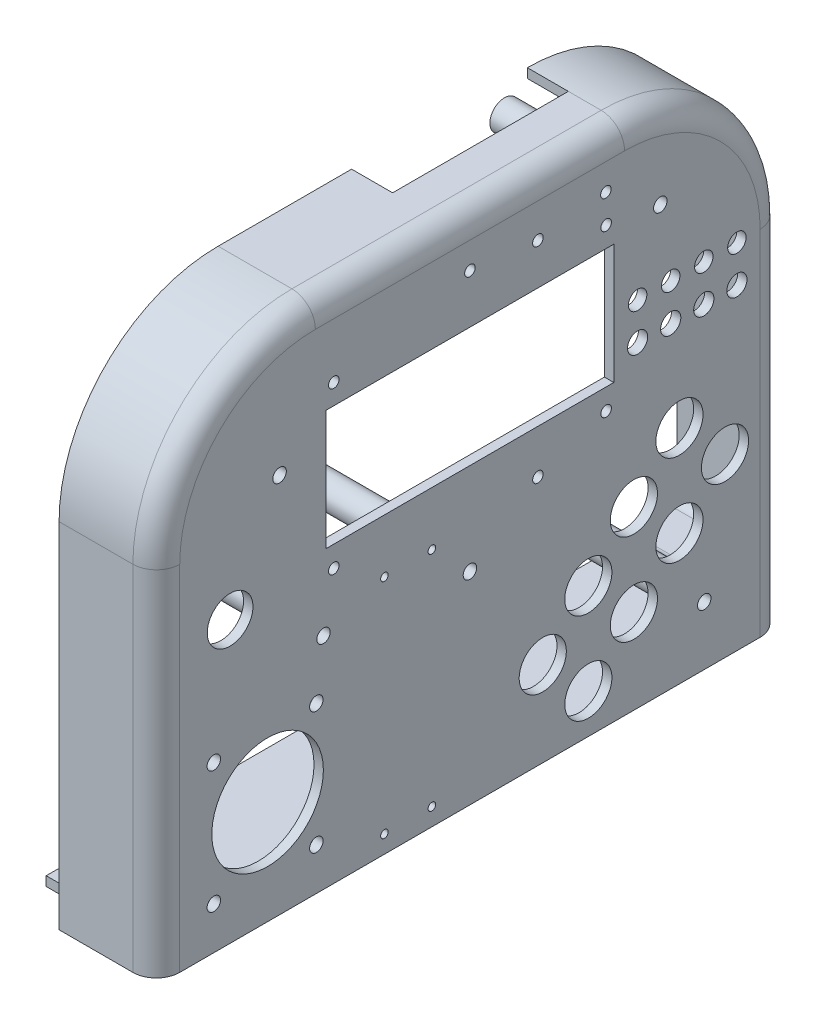
SolidWorks part; units mm, degrees
ref_plane "Front Plane" through (0, 0, 0) normal (0, 0, 1) x (1, 0, 0)
ref_plane "Top Plane" through (0, 0, 0) normal (0, 1, 0) x (1, 0, 0)
ref_plane "Right Plane" through (0, 0, 0) normal (1, 0, 0) x (0, 0, -1)
sketch "Sketch1" plane through (0, 0, 0) normal (1, 0, 0) x (0, 0, -1)
  line L0 (-107.09, -0.1) -> (107.09, -0.1) construction
  line L1 (-49.1, -20.45) -> (49.1, -20.45)
  line L2 (-49.1, -20.45) -> (-49.1, 20.45)
  line L3 (-49.1, 20.45) -> (49.1, 20.45)
  line L4 (49.1, -20.45) -> (49.1, 20.45)
  line L5 (-49.1, -20.45) -> (49.1, 20.45) construction
  line L6 (-49.1, 20.45) -> (49.1, -20.45) construction
  line L11 (-49.1, 29.95) -> (49.1, 29.95) construction
  line L12 (-49.1, 29.95) -> (-49.1, -30.15) construction
  line L13 (-49.1, -30.15) -> (49.1, -30.15) construction
  line L14 (49.1, 29.95) -> (49.1, -30.15) construction
  line L15 (-49.1, 20.45) -> (-82.6403, 20.45) construction
  line L16 (0, 0) -> (0, -0.1) construction
  line L17 (-46.5, -27.6) -> (46.5, -27.6) construction
  line L18 (-46.5, -27.6) -> (-46.5, 27.4) construction
  line L19 (-46.5, 27.4) -> (46.5, 27.4) construction
  line L20 (46.5, -27.6) -> (46.5, 27.4) construction
  line L21 (-46.5, -27.6) -> (46.5, 27.4) construction
  line L22 (-46.5, 27.4) -> (46.5, -27.6) construction
  line L23 (55.9773, -60.6563) -> (87.09, -60.6563) construction
  line L24 (71.5337, -45.1) -> (87.09, -60.6563) construction
  line L25 (55.9773, -60.6563) -> (71.5337, -45.1) construction
  line L26 (0, -0.1) -> (-71.6, -0.1) construction
  line L31 (0, -120.8) -> (0, 54.2) construction
  line L32 (-52.79, 54.2) -> (52.79, 54.2)
  line L33 (-69.95, -85.45) -> (-69.1, -85.45) construction
  line L34 (-52.45, -106.35) -> (-87.45, -106.35) construction
  line L35 (-52.45, -106.35) -> (-52.45, -64.55) construction
  line L36 (-52.45, -64.55) -> (-87.45, -64.55) construction
  line L37 (-87.45, -106.35) -> (-87.45, -64.55) construction
  line L38 (-52.45, -106.35) -> (-87.45, -64.55) construction
  line L39 (-52.45, -64.55) -> (-87.45, -106.35) construction
  line L40 (-107.09, -0.1) -> (-107.09, -120.8)
  line L41 (-107.09, -120.8) -> (107.09, -120.8)
  line L42 (107.09, -0.1) -> (107.09, -120.8)
  line L43 (0, -45.5) -> (0, -51.55) construction
  line L51 (46.42, 54.2) -> (46.42, 37.2) construction
  line L52 (0, 37.2) -> (46.42, 37.2) construction
  line L53 (23.21, 37.2) -> (23.21, -27.6) construction
  line L54 (-52.45, -106.35) -> (0, -106.35) construction
  line L56 (-29.2, -38.8) -> (-13, -38.8) construction
  line L58 (-29.2, -114.8) -> (-13, -114.8) construction
  line L59 (-29.2, -114.8) -> (-29.2, -38.8) construction
  line L60 (-29.2, -38.8) -> (-13, -38.8) construction
  line L61 (-13, -114.8) -> (-13, -38.8) construction
  line L62 (-29.2, -114.8) -> (-13, -38.8) construction
  line L63 (-29.2, -38.8) -> (-13, -114.8) construction
  line L65 (91.15, -3.25) -> (91.15, -9.25) construction
  circle A0 centre (46.5, 27.4) radius 1.8
  circle A1 centre (-46.5, -27.6) radius 1.8
  circle A2 centre (-46.5, 27.4) radius 1.8
  circle A3 centre (46.5, -27.6) radius 1.8
  circle A4 centre (57.25, -0.1) radius 3.15
  circle A5 centre (68.55, -0.1) radius 3.15
  circle A6 centre (79.85, -0.1) radius 3.15
  circle A7 centre (91.15, -0.1) radius 3.15
  circle A9 centre (46.5, 27.4) radius 2.55 construction
  circle A10 centre (46.5, -27.6) radius 2.55 construction
  circle A11 centre (71.5337, -45.1) radius 8.05
  circle A12 centre (87.09, -60.6563) radius 8.05
  circle A13 centre (71.5337, -76.2127) radius 8.05
  circle A14 centre (55.9773, -91.769) radius 8.05
  circle A15 centre (40.421, -107.3254) radius 8.05
  circle A16 centre (55.9773, -60.6563) radius 8.05
  circle A17 centre (40.421, -76.2127) radius 8.05
  circle A18 centre (24.8646, -91.769) radius 8.05
  circle A25 centre (-87.45, -106.35) radius 2.3
  circle A26 centre (-52.45, -106.35) radius 2.3
  circle A27 centre (-52.45, -64.55) radius 2.3
  circle A28 centre (-87.45, -64.55) radius 2.3
  circle A29 centre (-69.1, -85.45) radius 19.05
  arc A30 (52.79, 54.2) -> (107.09, -0.1) centre (52.79, -0.1) cw
  arc A31 (-52.79, 54.2) -> (-107.09, -0.1) centre (-52.79, -0.1) ccw
  circle A41 centre (-81.9, -25.1) radius 7.8
  circle A44 centre (46.42, 37.2) radius 1.8
  circle A45 centre (0, 37.2) radius 1.8
  circle A46 centre (23.21, 34.55) radius 1.8
  circle A47 centre (23.21, -35.45) radius 1.8
  circle A48 centre (-29.2, -38.8) radius 1.3
  circle A49 centre (-13, -38.8) radius 1.3
  circle A50 centre (-13, -114.8) radius 1.3
  circle A51 centre (-29.2, -114.8) radius 1.3
  circle A52 centre (91.15, -12.7) radius 3.45
  circle A53 centre (79.85, -12.7) radius 3.45
  circle A54 centre (68.55, -12.7) radius 3.45
  circle A55 centre (57.25, -12.7) radius 3.45
  point P1 (0, 0)
  point P11 (46.5, 27.4)
  point P12 (-46.5, -27.6)
  point P16 (-48.3, -27.6)
  point P17 (-46.5, -29.4)
  point P18 (48.3, 27.4)
  point P19 (46.5, 29.2)
  point P22 (-46.5, 29.2)
  point P23 (-48.3, 27.4)
  point P26 (46.5, -29.4)
  point P27 (48.3, -27.6)
  point P30 (54.1, -0.1)
  point P31 (60.4, -0.1)
  point P32 (57.25, 3.05)
  point P36 (65.4, -0.1)
  point P37 (71.7, -0.1)
  point P40 (76.7, -0.1)
  point P41 (83, -0.1)
  point P44 (88, -0.1)
  point P45 (88, -0.1)
  point P47 (-74.1, -25.1)
  point P48 (-64.1, -0.1)
  point P49 (-71.6, 7.4)
  point P52 (0, -0.1)
  point P67 (71.5337, -45.1)
  point P84 (-82.6403, 12.7)
  point P86 (0, -0.1)
  point P92 (0, -33.3)
  point P96 (-69.95, -85.45)
  point P97 (-52.45, -64.55)
  point P98 (-87.45, -64.55)
  point P99 (-87.45, -106.35)
  point P100 (-52.45, -106.35)
  point P107 (0, -45.5)
  point P108 (-81.9, 7.7)
  point P109 (0, 0)
  point P110 (0, 0)
  point P111 (57.25, -0.1)
  point P112 (57.25, -0.1)
  point P116 (-71.6, 7.4)
  point P119 (-74.1, -25.1)
  point P120 (-81.9, -17.3)
  point P123 (23.21, 37.2)
  point P124 (0, 37.2)
  point P125 (0, -33.3)
  point P126 (0, 0)
  point P127 (46.42, 37.2)
  point P134 (-26.225, -106.35)
  point P136 (-81.9, -32.9)
  point P141 (-21.1, -38.8)
  point P147 (-21.1, -76.8)
  point P155 (60.7, -12.7)
  point P156 (65.1, -12.7)
  point P157 (72, -12.7)
  point P158 (76.4, -12.7)
  point P159 (83.3, -12.7)
  point P160 (87.7, -12.7)
  point P161 (61.6695, -54.9641)
  point P162 (65, -56.4773)
  point P163 (65.8414, -50.7922)
  point P164 (71.5337, -53.15)
  point P165 (0, 0)
  point P166 (0, 0)
  point P167 (57.25, -9.25)
  point P168 (57.25, -3.25)
  point P171 (0, 0)
  point P172 (0, 0)
  dimension "D4" = 3.6
  dimension "D13" = 19.09
  dimension "D14" = 2
  dimension "D16" = 20
  dimension "D19" = 6.3
  dimension "D29" = 18.35
  dimension "D30" = 38.1
  dimension "D31" = 45
  dimension "D32" = 15.6
  dimension "D11" = 16.1
  dimension "D12" = 22
  dimension "D21" = 65
  dimension "D26" = 4.6
  dimension "D34" = 25
  dimension "D36" = 25
  dimension "D37" = 175
  dimension "D42" = 54.3
  dimension "D49" = 70
  dimension "D53" = 2.6
  dimension "D48" = 6.9
  dimension "D59" = 7.3321
  dimension "D1" = 98.2
  dimension "D2" = 40.9
  dimension "D5" = 55
  dimension "D6" = 93
  dimension "D7" = 60.1
  dimension "D8" = 98.2
  dimension "D9" = 9.7
  dimension "D10" = 0
  dimension "D15" = 4
  dimension "D17" = 45
  dimension "D18" = 45
  dimension "D20" = 5
  dimension "D22" = 20
  dimension "D23" = 5
  dimension "D24" = 5
  dimension "D25" = 5
  dimension "D27" = 35
  dimension "D28" = 41.8
  dimension "D33" = 25
  dimension "D35" = 33.5403
  dimension "D38" = 8
  dimension "D40" = 214.18
  dimension "D44" = 6.05
  dimension "D45" = 12.2
  dimension "D46" = 46.42
  dimension "D50" = 15
  dimension "D51" = 76
  dimension "D52" = 16.2
  dimension "D54" = 6
  dimension "D55" = 13
  dimension "D56" = 3.35
  dimension "D57" = 5.9
  dimension "D58" = 6
extrude "Boss-Extrude1" add sketch "Sketch1" along normal blind 3.2
sketch "Sketch3" plane through (0, 0, 0) normal (-1, 0, 0) x (0, 0, 1)
  line L0 (-103.89, -0.1) -> (-103.89, -117.6)
  line L1 (-103.89, -117.6) -> (103.89, -117.6)
  line L2 (103.89, -117.6) -> (103.89, -0.1)
  line L3 (52.79, 51) -> (-52.79, 51)
  line L4 (-107.09, -0.1) -> (-107.09, -120.8)
  line L5 (-107.09, -120.8) -> (107.09, -120.8)
  line L6 (107.09, -120.8) -> (107.09, -0.1)
  line L7 (52.79, 54.2) -> (-52.79, 54.2)
  line L8 (-107.09, -0.1) -> (-107.09, -120.8)
  line L9 (-107.09, -120.8) -> (107.09, -120.8)
  line L10 (107.09, -120.8) -> (107.09, -0.1)
  line L11 (52.79, 54.2) -> (-52.79, 54.2)
  arc A0 (103.89, -0.1) -> (52.79, 51) centre (52.79, -0.1) ccw
  arc A1 (-52.79, 51) -> (-103.89, -0.1) centre (-52.79, -0.1) ccw
  arc A2 (-52.79, 54.2) -> (-107.09, -0.1) centre (-52.79, -0.1) ccw
  arc A3 (107.09, -0.1) -> (52.79, 54.2) centre (52.79, -0.1) ccw
  arc A4 (-52.79, 54.2) -> (-107.09, -0.1) centre (-52.79, -0.1) ccw
  arc A5 (107.09, -0.1) -> (52.79, 54.2) centre (52.79, -0.1) ccw
  dimension "D3" = 207.78
  dimension "D4" = 168.6
  dimension "D1" = 0
  dimension "D2" = 3.2
extrude "Boss-Extrude2" add sketch "Sketch3" along normal blind 30
fillet "Fillet1" radius 4.8 5 edges at (0, -58.85, -103.89) (0, 36.0332, -88.9232) (0, 51, 0) (0, 36.0332, 88.9232) (0, -58.85, 103.89)
sketch "Sketch20" plane through (3.2, 0, 0) normal (1, 0, 0) x (0, 0, -1)
  line L0 (-107.09, -120.8) -> (107.09, -120.8) construction
  line L1 (-65, -100.8) -> (65, -100.8) construction
  line L2 (-65, -100.8) -> (-65, 9.2) construction
  line L3 (-65, 9.2) -> (65, 9.2) construction
  line L4 (65, -100.8) -> (65, 9.2) construction
  line L5 (-65, -100.8) -> (65, 9.2) construction
  line L6 (-65, 9.2) -> (65, -100.8) construction
  line L8 (0, 0) -> (0, -45.8) construction
  line L9 (0, -45.8) -> (0, -51.8) construction
  circle A0 centre (-65, 9.2) radius 2.3
  circle A4 centre (0, -51.8) radius 2.3
  circle A5 centre (-50, -45.8) radius 2.3
  circle A6 centre (65, 24.2) radius 2.3
  circle A7 centre (80, -100.8) radius 2.3
  point P0 (0, -45.8)
  point P8 (0, 0)
  point P20 (-65, -45.8)
  dimension "D1" = 4.6
  dimension "D2" = 20
  dimension "D3" = 110
  dimension "D4" = 130
  dimension "D5" = 6
  dimension "D6" = 15
  dimension "D7" = 50
  dimension "D8" = 15
extrude "Cut-Extrude8" cut sketch "Sketch20" against normal blind 10
sketch "Sketch6" plane through (0, 0, 0) normal (-1, 0, 0) x (0, 0, 1)
  circle A4 centre (65, 9.2) radius 5
  circle A5 centre (65, 9.2) radius 2.3
  circle A8 centre (-65, 24.2) radius 5
  circle A9 centre (-65, 24.2) radius 2.3
  circle A12 centre (-80, -100.8) radius 5
  circle A13 centre (-80, -100.8) radius 2.3
  circle A14 centre (50, -45.8) radius 5
  circle A15 centre (50, -45.8) radius 2.3
  circle A18 centre (0, -51.8) radius 2.3
  circle A19 centre (0, -51.8) radius 5
  point P2 (55, -45.8)
  point P6 (-80, -100.8)
  point P15 (65, 9.2)
  point P17 (0, -46.8)
  point P23 (65, -100.8)
  point P26 (0, -51.8)
  point P30 (65, 9.2)
  point P33 (45, -45.8)
  point P34 (50, -50.8)
  point P36 (65, 14.2)
  point P38 (50, -40.8)
  point P39 (70, 9.2)
  point P40 (-65, 24.2)
  point P41 (-65, 29.2)
  point P42 (60, 9.2)
  point P44 (65, 4.2)
  point P45 (-70, 24.2)
  point P46 (-80, -105.8)
  point P47 (-85, -100.8)
  point P49 (-5, -51.8)
  point P51 (0, -56.8)
  point P52 (5, -51.8)
  point P54 (-60, 24.2)
  point P59 (-65, 19.2)
  point P60 (-75, -100.8)
  point P61 (-80, -95.8)
  dimension "D10" = 10
  dimension "D9" = 4.6
extrude "Boss-Extrude3" add sketch "Sketch6" along normal blind 50
sketch "Sketch12" plane through (-30, 0, 0) normal (-1, 0, 0) x (0, 0, 1)
  line L0 (96.49, -117.6) -> (96.49, -120.8)
  line L1 (-96.49, -117.6) -> (-96.49, -120.8)
  line L2 (107.09, -120.8) -> (96.49, -120.8) construction
  line L3 (-96.49, -117.6) -> (96.49, -117.6)
  line L4 (-96.49, -120.8) -> (-107.09, -120.8) construction
  line L13 (52.79, 54.2) -> (-52.79, 54.2)
  line L14 (-107.09, -0.1) -> (-107.09, -120.8)
  line L15 (-107.09, -120.8) -> (107.09, -120.8)
  line L16 (107.09, -120.8) -> (107.09, -0.1)
  line L26 (-107.09, -0.1) -> (-107.09, -120.8) construction
  line L27 (-96.49, -120.8) -> (96.49, -120.8)
  line L28 (107.09, -120.8) -> (107.09, -0.1) construction
  arc A4 (-52.79, 54.2) -> (-107.09, -0.1) centre (-52.79, -0.1) ccw
  arc A5 (107.09, -0.1) -> (52.79, 54.2) centre (52.79, -0.1) ccw
  point P15 (-96.49, -117.6)
  point P16 (96.49, -117.6)
  dimension "D2" = 10.6
  dimension "D3" = 10.6
  dimension "D4" = 3.2
  dimension "D1" = 0
extrude "Boss-Extrude7" add sketch "Sketch12" along normal blind 15
sketch "Sketch8" plane through (0, -120.8, 0) normal (0, -1, 0) x (1, 0, 0)
  line L0 (3.2, 99.09) -> (-30, 99.09) construction
  line L1 (-30, -107.09) -> (-30, -96.49) construction
  line L2 (-4.8, 107.09) -> (-4.8, 47.09) construction
  line L3 (-6, 92.09) -> (-24.6, 92.09) construction
  line L5 (-34.6, 92.09) -> (-14.6, 92.09) construction
  line L6 (3.2, -98.5496) -> (-30, -98.5496) construction
  line L7 (-4.8, -107.09) -> (-4.8, -47.09) construction
  line L8 (-6, -92.09) -> (-24.6, -92.09) construction
  line L9 (3.2, -107.09) -> (-30, -107.09) construction
  line L10 (-14.6, -92.09) -> (-34.6, -92.09) construction
  line L11 (3.2, 107.09) -> (-30, 107.09) construction
  circle A0 centre (-14.6, 92.09) radius 2.3
  circle A1 centre (-34.6, 92.09) radius 2.3
  circle A2 centre (-14.6, -92.09) radius 2.3
  circle A3 centre (-34.6, -92.09) radius 2.3
  point P8 (-4.8, 77.1)
  point P9 (-13.4, 99.09)
  point P16 (-24.6, 92.09)
  point P24 (-4.8, -77.09)
  point P25 (-13.4, -98.5496)
  point P32 (-24.6, -92.09)
  dimension "D3" = 4.6
  dimension "D6" = 4.6
  dimension "D1" = 60
  dimension "D2" = 20
  dimension "D4" = 60
  dimension "D5" = 20
  dimension "D7" = 15
  dimension "D8" = 15
  dimension "D9" = 19.8
  dimension "D10" = 19.8
extrude "Cut-Extrude2" cut sketch "Sketch8" against normal blind 10
sketch "Sketch19" plane through (0, 54.2, 0) normal (0, 1, 0) x (1, 0, 0)
  line L0 (-30, 52.79) -> (-16, 52.79)
  line L1 (3.2, 52.79) -> (-30, 52.79) construction
  line L2 (-16, 52.79) -> (-16, -7.21)
  line L3 (-16, -7.21) -> (-30, -7.21)
  line L4 (-30, -52.79) -> (-30, 52.79) construction
  line L5 (-30, -7.21) -> (-30, 52.79)
  dimension "D1" = 14
  dimension "D2" = 60
extrude "Cut-Extrude7" cut sketch "Sketch19" against normal blind 10
sketch "Sketch21" plane through (0, 0, 0) normal (1, 0, 0) x (0, 0, -1)
  line L0 (103.89, -0.1) -> (103.89, -117.6) construction
  line L1 (103.89, -0.1) -> (103.89, -117.6) construction
  line L2 (85, -100.8) -> (103.89, -100.8) construction
  line L4 (103.89, -102.6) -> (85, -102.6)
  line L5 (103.89, -102.6) -> (103.89, -99)
  line L6 (103.89, -99) -> (85, -99)
  line L7 (85, -102.6) -> (85, -99) construction
  line L8 (103.89, -102.6) -> (85, -99) construction
  line L9 (103.89, -99) -> (85, -102.6) construction
  line L11 (85, -99) -> (84.6648, -99)
  line L12 (85, -102.6) -> (84.6648, -102.6)
  line L13 (65, 29.2) -> (65, 50.6648) construction
  line L15 (63.2, 28.8648) -> (66.8, 28.8648)
  line L16 (63.2, 28.8648) -> (63.2, 51)
  line L17 (63.2, 51) -> (66.8, 51)
  line L18 (66.8, 28.8648) -> (66.8, 51)
  line L19 (63.2, 28.8648) -> (66.8, 51) construction
  line L20 (63.2, 51) -> (66.8, 28.8648) construction
  line L21 (52.79, 51) -> (-7.21, 51) construction
  line L22 (-70, 9.2) -> (-103.0366, 9.2) construction
  line L23 (-103.89, -117.6) -> (-103.89, -0.1) construction
  line L24 (-69.6648, 7.4) -> (-103.89, 7.4)
  line L25 (-69.6648, 7.4) -> (-69.6648, 11)
  line L26 (-69.6648, 11) -> (-103.89, 11)
  line L27 (-103.89, 7.4) -> (-103.89, 11)
  line L28 (-69.6648, 7.4) -> (-103.89, 11) construction
  line L29 (-69.6648, 11) -> (-103.89, 7.4) construction
  circle A0 centre (80, -100.8) radius 5 construction
  arc A1 (84.6648, -102.6) -> (84.6648, -99) centre (80, -100.8) ccw
  circle A3 centre (-65, 9.2) radius 5 construction
  circle A4 centre (65, 24.2) radius 5 construction
  arc A5 (-52.79, 51) -> (-103.89, -0.1) centre (-52.79, -0.1) ccw construction
  arc A6 (-52.79, 51) -> (-103.89, -0.1) centre (-52.79, -0.1) ccw construction
  point P0 (85, -100.8)
  point P8 (85, -100.8)
  point P14 (94.445, -100.8)
  point P23 (65, 29.2)
  point P26 (65, 39.9324)
  point P38 (0, 0)
  point P45 (0, 0)
  point P46 (-86.5183, 9.2)
  point P47 (0, 0)
  point P48 (0, 0)
  point P49 (0, 0)
  point P50 (-86.5183, 7.2346)
  point P51 (0, 0)
  point P52 (-86.7774, 9.2)
  point P53 (-86.5183, 9.2)
  point P54 (0, 0)
  point P59 (-86.7774, 9.2)
  dimension "D1" = 3.6
  dimension "D3" = 10
  dimension "D6" = 10
  dimension "D2" = 18.89
  dimension "D4" = 3.6
  dimension "D5" = 3.6
extrude "Boss-Extrude8" add sketch "Sketch21" against normal up to surface (30 mm away)
fillet "Fillet5" radius 3 9 edges at (0, -99, -91.8774) (-1.4059, -99, -102.4841) (0, -102.6, -91.8774) (-1.4059, -102.6, -102.4841) (-17.4, -99, -103.89) (-17.4, -102.6, -103.89) (0, -100.8, -75) (-15, -102.6, -84.6648) (-15, -99, -84.6648)
fillet "Fillet6" radius 8 5 edges at (3.2, -60.45, -107.09) (3.2, 38.2959, -91.1859) (3.2, -60.45, 107.09) (3.2, 38.2959, 91.1859) (3.2, 54.2, 0)
